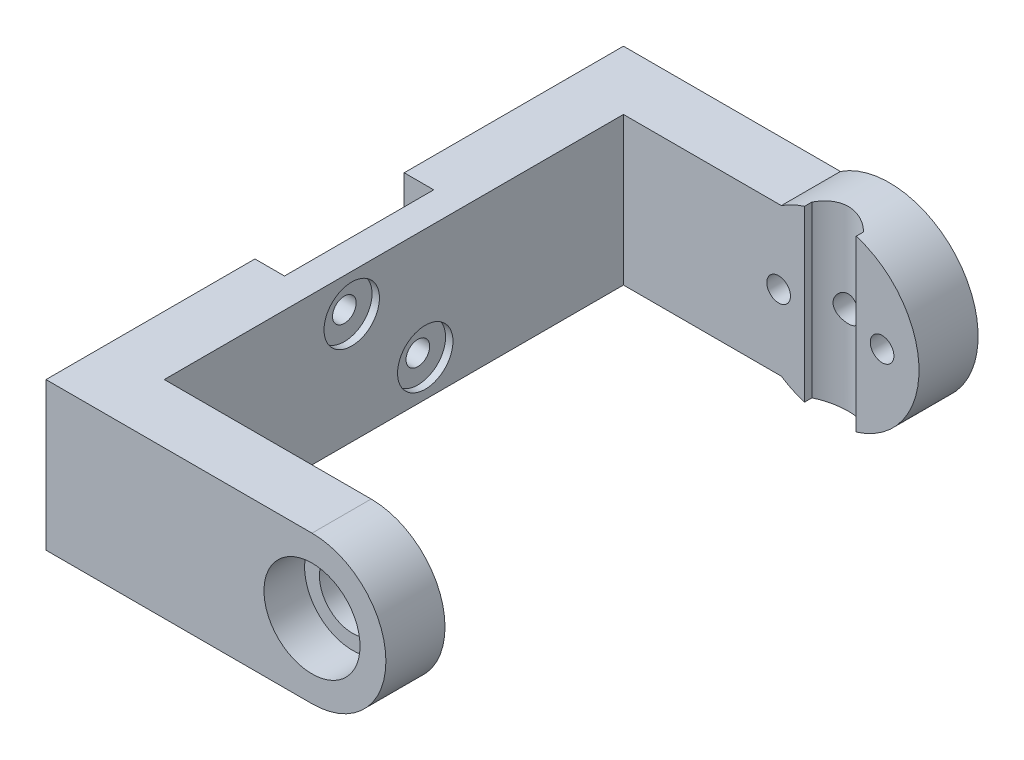
SolidWorks part; units mm, degrees
material "ABS"
ref_plane "Płaszczyzna przednia" through (0, 0, 0) normal (0, 0, 1) x (1, 0, 0)
ref_plane "Płaszczyzna górna" through (0, 0, 0) normal (0, 1, 0) x (1, 0, 0)
ref_plane "Płaszczyzna prawa" through (0, 0, 0) normal (1, 0, 0) x (0, 0, -1)
sketch "Szkic25" plane through (0, 0, 0) normal (1, 0, 0) x (0, 0, -1)
  line L1 (31.075, 10) -> (-31.075, 10)
  line L2 (31.075, 10) -> (31.075, -10)
  line L3 (31.075, -10) -> (-31.075, -10)
  line L4 (-31.075, 10) -> (-31.075, -10)
  line L5 (31.075, 10) -> (-31.075, -10) construction
  line L6 (31.075, -10) -> (-31.075, 10) construction
  point P0 (0, 0)
  dimension "D1" = 62.15
  dimension "D2" = 20
extrude "Dodanie-wyciągnięcie7" add sketch "Szkic25" along normal blind 8
sketch "Szkic14" plane through (0, 0, -31.075) normal (0, 0, -1) x (-1, 0, 0)
  line L0 (0, 10) -> (0, -10)
  line L1 (0, 10) -> (-29.3668, 10)
  line L2 (0, -10) -> (-29.3668, -10)
  line L6 (0, 0) -> (-36, 0) construction
  arc A1 (-29.3668, 10) -> (-29.3668, -10) centre (-36, 0) ccw
  circle A2 centre (-36, 0) radius 1.75
  dimension "D2" = 12
  dimension "D3" = 3.5
  dimension "D1" = 36
extrude "Dodanie-wyciągnięcie5" add sketch "Szkic14" along normal blind 8
sketch "Szkic16" plane through (0, 0, 31.075) normal (0, 0, 1) x (1, 0, 0)
  line L0 (0, 10) -> (0, -10)
  line L1 (0, 10) -> (36, 10)
  line L2 (0, -10) -> (36, -10)
  arc A0 (36, -10) -> (36, 10) centre (36, 0) ccw
  circle A1 centre (36, 0) radius 1.75 construction
  circle A2 centre (36, 0) radius 4.5
  dimension "D1" = 9
extrude "Dodanie-wyciągnięcie6" add sketch "Szkic16" along normal blind 8 contours A2 | A0 L1 L0 L2
sketch "Szkic19" plane through (0, 0, 39.075) normal (0, 0, 1) x (1, 0, 0)
  circle A0 centre (36, 0) radius 6.5
  dimension "D1" = 13
extrude "Wytnij-wyciągnięcie8" cut sketch "Szkic19" against normal offset from surface (5.5 mm away) 2.5 up to face at (24.5, 0, 31.075)
sketch "Szkic20" plane through (0, 0, -39.075) normal (0, 0, -1) x (-1, 0, 0)
  line L0 (0, 0) -> (-48, 0) construction
  line L1 (0, -10) -> (0, 10) construction
  line L2 (-36, 12) -> (-36, -12) construction
  circle A0 centre (-43, 0) radius 1.6
  circle A1 centre (-29, 0) radius 1.6
  arc A2 (-29.3668, 10) -> (-29.3668, -10) centre (-36, 0) ccw construction
  dimension "D1" = 3.2
  dimension "D2" = 7
extrude "Wytnij-wyciągnięcie9" cut sketch "Szkic20" against normal up to next contours A1 | A0
sketch "Szkic21" plane through (0, 0, -39.075) normal (0, 0, -1) x (-1, 0, 0)
  circle A0 centre (-43, 0) radius 3.75
  circle A1 centre (-29, 0) radius 3.75
  dimension "D1" = 7.5
extrude "Wytnij-wyciągnięcie10" cut sketch "Szkic21" against normal blind 3.5
sketch "Szkic22" plane through (0, 0, -39.075) normal (0, 0, -1) x (-1, 0, 0)
  circle A0 centre (-36, 0) radius 3
  dimension "D1" = 6
extrude "Wytnij-wyciągnięcie11" cut sketch "Szkic22" against normal blind 2
ref_plane "Płaszczyzna3" through (0, 12, 0) normal (0, 1, 0) x (1, 0, 0)
sketch "Szkic23" plane through (0, 12, 0) normal (0, 1, 0) x (1, 0, 0)
  line L0 (32.5, 31.075) -> (39.5, 31.075)
  line L1 (32.5, 31.075) -> (32.5, 32.075)
  line L2 (39.5, 31.075) -> (39.5, 32.075)
  line L4 (29.3668, 31.075) -> (48, 31.075) construction
  line L5 (36, 39.075) -> (36, 31.075) construction
  line L6 (39, 39.075) -> (33, 39.075) construction
  line L7 (36, 31.075) -> (36, 27.9434) construction
  arc A0 (39.5, 32.075) -> (32.5, 32.075) centre (36, 28.5043) ccw
  dimension "D2" = 5
  dimension "D1" = 7
  dimension "D3" = 1
extrude "Wytnij-wyciągnięcie12" cut sketch "Szkic23" against normal up to next
sketch "Szkic26" plane through (0, 0, 0) normal (-1, 0, 0) x (0, 0, 1)
  line L0 (-39.075, 10) -> (39.075, 10) construction
  line L1 (-9.4, 10) -> (10.8, 10)
  line L2 (-9.4, 10) -> (-9.4, -10)
  line L3 (-9.4, -10) -> (10.8, -10)
  line L4 (10.8, 10) -> (10.8, -10)
  line L5 (39.075, -10) -> (-39.075, -10) construction
  line L6 (10.8, 10) -> (-9.4, -10) construction
  line L7 (-9.4, 10) -> (10.8, -10) construction
  line L10 (0, -13.2) -> (0, 13.2) construction
  point P10 (0.7, 0)
  dimension "D1" = 20.2
  dimension "D2" = 0.7
extrude "Wytnij-wyciągnięcie13" cut sketch "Szkic26" against normal blind 4
sketch "Szkic27" plane through (4, 0, 0) normal (-1, 0, 0) x (0, 0, 1)
  line L0 (-9.4, 0) -> (10.8, 0) construction
  line L1 (-9.4, 10) -> (10.8, -10) construction
  line L2 (10.8, -10) -> (10.8, 10) construction
  line L4 (-9.4, 10) -> (-9.4, -10) construction
  line L5 (0.7, 10) -> (0.7, -10) construction
  line L6 (10.8, 10) -> (-9.4, 10) construction
  line L7 (-9.4, -10) -> (10.8, -10) construction
  circle A0 centre (5.7, 5) radius 1.6
  circle A1 centre (-4.25, -5.0495) radius 1.6
  dimension "D1" = 3.2
  dimension "D2" = 5
  dimension "D3" = 5
extrude "Wytnij-wyciągnięcie14" cut sketch "Szkic27" against normal up to next
sketch "Szkic28" plane through (8, 0, 0) normal (1, 0, 0) x (0, 0, -1)
  circle A0 centre (-5.7, 5) radius 3.75
  circle A1 centre (4.25, -5.0495) radius 3.75
  dimension "D1" = 7.5
extrude "Wytnij-wyciągnięcie15" cut sketch "Szkic28" against normal blind 1
sketch "Szkic29" plane through (0, 0, 0) normal (0, 0, 1) x (1, 0, 0)
  point P0 (36, 0)
